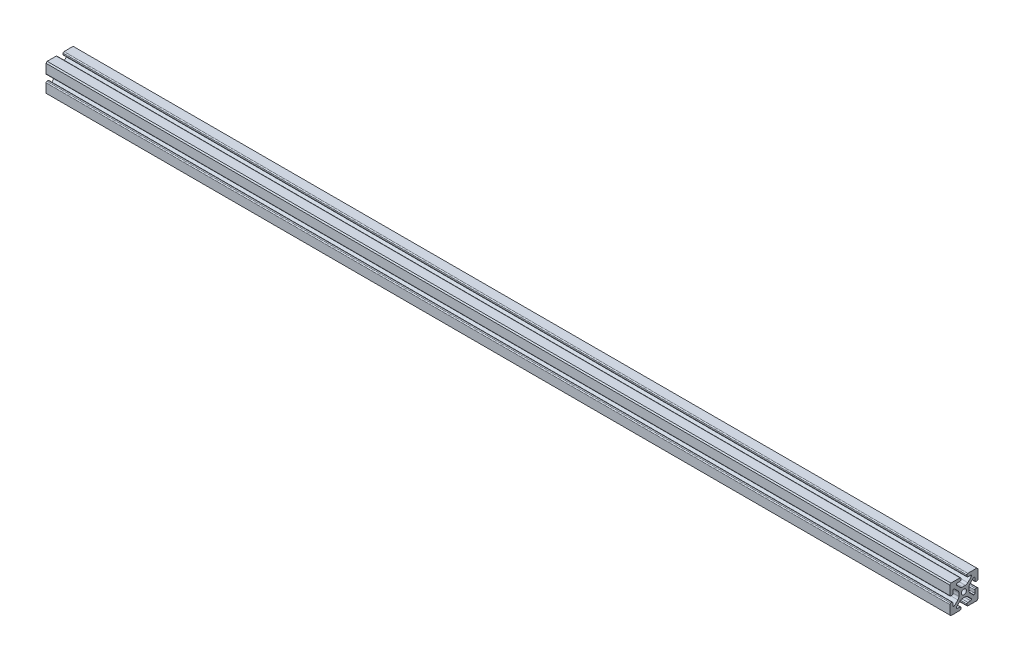
SolidWorks part; units mm, degrees
ref_plane "Front Plane" through (0, 0, 0) normal (0, 0, 1) x (1, 0, 0)
ref_plane "Top Plane" through (0, 0, 0) normal (0, 1, 0) x (1, 0, 0)
ref_plane "Right Plane" through (0, 0, 0) normal (1, 0, 0) x (0, 0, -1)
ref_plane "Plane1" through (0, 0, 0) normal (-1, 0, 0) x (0, -1, 0)
sketch "Sketch1" plane through (0, 0, 0) normal (-1, 0, 0) x (0, -1, 0)
  line L0 (19.05, 5.334) -> (19.05, 17.526)
  line L1 (19.05, 17.526) -> (17.526, 19.05)
  line L2 (17.526, 19.05) -> (5.334, 19.05)
  line L3 (4.064, 17.78) -> (4.064, 16.1266)
  line L4 (5.334, 14.8566) -> (9.0964, 14.8566)
  line L5 (10.287, 13.666) -> (10.287, 13.6538)
  line L6 (9.9383, 12.8119) -> (5.2776, 8.1513)
  line L7 (1.91, 6.7564) -> (-1.91, 6.7564)
  line L8 (-5.2776, 8.1513) -> (-9.9383, 12.8119)
  line L9 (-10.287, 13.6538) -> (-10.287, 13.666)
  line L10 (-9.0964, 14.8566) -> (-5.334, 14.8566)
  line L11 (-4.064, 16.1266) -> (-4.064, 17.78)
  line L12 (-5.334, 19.05) -> (-17.526, 19.05)
  line L13 (-17.526, 19.05) -> (-19.05, 17.526)
  line L14 (-19.05, 17.526) -> (-19.05, 5.334)
  line L15 (-17.78, 4.064) -> (-16.1266, 4.064)
  line L16 (-14.8566, 5.334) -> (-14.8566, 9.0964)
  line L17 (-13.666, 10.287) -> (-13.6538, 10.287)
  line L18 (-12.8119, 9.9383) -> (-8.1513, 5.2776)
  line L19 (-6.7564, 1.91) -> (-6.7564, -1.91)
  line L20 (-8.1513, -5.2776) -> (-12.8119, -9.9383)
  line L21 (-13.6538, -10.287) -> (-13.666, -10.287)
  line L22 (-14.8566, -9.0964) -> (-14.8566, -5.334)
  line L23 (-16.1266, -4.064) -> (-17.78, -4.064)
  line L24 (-19.05, -5.334) -> (-19.05, -17.526)
  line L25 (-19.05, -17.526) -> (-17.526, -19.05)
  line L26 (-17.526, -19.05) -> (-5.334, -19.05)
  line L27 (-4.064, -17.78) -> (-4.064, -16.1266)
  line L28 (-5.334, -14.8566) -> (-9.0964, -14.8566)
  line L29 (-10.287, -13.666) -> (-10.287, -13.6538)
  line L30 (-9.9383, -12.8119) -> (-5.2776, -8.1513)
  line L31 (-1.91, -6.7564) -> (1.91, -6.7564)
  line L32 (5.2776, -8.1513) -> (9.9383, -12.8119)
  line L33 (10.287, -13.6538) -> (10.287, -13.666)
  line L34 (9.0964, -14.8566) -> (5.334, -14.8566)
  line L35 (4.064, -16.1266) -> (4.064, -17.78)
  line L36 (5.334, -19.05) -> (17.526, -19.05)
  line L37 (17.526, -19.05) -> (19.05, -17.526)
  line L38 (19.05, -17.526) -> (19.05, -5.334)
  line L39 (17.78, -4.064) -> (16.1266, -4.064)
  line L40 (14.8566, -5.334) -> (14.8566, -9.0964)
  line L41 (13.666, -10.287) -> (13.6538, -10.287)
  line L42 (12.8119, -9.9383) -> (8.1513, -5.2776)
  line L43 (6.7564, -1.91) -> (6.7564, 1.91)
  line L44 (8.1513, 5.2776) -> (12.8119, 9.9383)
  line L45 (13.6538, 10.287) -> (13.666, 10.287)
  line L46 (14.8566, 9.0964) -> (14.8566, 5.334)
  line L47 (16.1266, 4.064) -> (17.78, 4.064)
  arc A0 (17.78, 4.064) -> (19.05, 5.334) centre (17.78, 5.334) ccw
  arc A1 (5.334, 19.05) -> (4.064, 17.78) centre (5.334, 17.78) ccw
  arc A2 (4.064, 16.1266) -> (5.334, 14.8566) centre (5.334, 16.1266) ccw
  arc A3 (9.0964, 14.8566) -> (10.287, 13.666) centre (9.0964, 13.666) cw
  arc A4 (10.287, 13.6538) -> (9.9383, 12.8119) centre (9.0964, 13.6538) cw
  arc A5 (5.2776, 8.1513) -> (1.91, 6.7564) centre (1.91, 11.5189) cw
  arc A6 (-1.91, 6.7564) -> (-5.2776, 8.1513) centre (-1.91, 11.5189) cw
  arc A7 (-9.9383, 12.8119) -> (-10.287, 13.6538) centre (-9.0964, 13.6538) cw
  arc A8 (-10.287, 13.666) -> (-9.0964, 14.8566) centre (-9.0964, 13.666) cw
  arc A9 (-5.334, 14.8566) -> (-4.064, 16.1266) centre (-5.334, 16.1266) ccw
  arc A10 (-4.064, 17.78) -> (-5.334, 19.05) centre (-5.334, 17.78) ccw
  arc A11 (-19.05, 5.334) -> (-17.78, 4.064) centre (-17.78, 5.334) ccw
  arc A12 (-16.1266, 4.064) -> (-14.8566, 5.334) centre (-16.1266, 5.334) ccw
  arc A13 (-14.8566, 9.0964) -> (-13.666, 10.287) centre (-13.666, 9.0964) cw
  arc A14 (-13.6538, 10.287) -> (-12.8119, 9.9383) centre (-13.6538, 9.0964) cw
  arc A15 (-8.1513, 5.2776) -> (-6.7564, 1.91) centre (-11.5189, 1.91) cw
  arc A16 (-6.7564, -1.91) -> (-8.1513, -5.2776) centre (-11.5189, -1.91) cw
  arc A17 (-12.8119, -9.9383) -> (-13.6538, -10.287) centre (-13.6538, -9.0964) cw
  arc A18 (-13.666, -10.287) -> (-14.8566, -9.0964) centre (-13.666, -9.0964) cw
  arc A19 (-14.8566, -5.334) -> (-16.1266, -4.064) centre (-16.1266, -5.334) ccw
  arc A20 (-17.78, -4.064) -> (-19.05, -5.334) centre (-17.78, -5.334) ccw
  arc A21 (-5.334, -19.05) -> (-4.064, -17.78) centre (-5.334, -17.78) ccw
  arc A22 (-4.064, -16.1266) -> (-5.334, -14.8566) centre (-5.334, -16.1266) ccw
  arc A23 (-9.0964, -14.8566) -> (-10.287, -13.666) centre (-9.0964, -13.666) cw
  arc A24 (-10.287, -13.6538) -> (-9.9383, -12.8119) centre (-9.0964, -13.6538) cw
  arc A25 (-5.2776, -8.1513) -> (-1.91, -6.7564) centre (-1.91, -11.5189) cw
  arc A26 (1.91, -6.7564) -> (5.2776, -8.1513) centre (1.91, -11.5189) cw
  arc A27 (9.9383, -12.8119) -> (10.287, -13.6538) centre (9.0964, -13.6538) cw
  arc A28 (10.287, -13.666) -> (9.0964, -14.8566) centre (9.0964, -13.666) cw
  arc A29 (5.334, -14.8566) -> (4.064, -16.1266) centre (5.334, -16.1266) ccw
  arc A30 (4.064, -17.78) -> (5.334, -19.05) centre (5.334, -17.78) ccw
  arc A31 (19.05, -5.334) -> (17.78, -4.064) centre (17.78, -5.334) ccw
  arc A32 (16.1266, -4.064) -> (14.8566, -5.334) centre (16.1266, -5.334) ccw
  arc A33 (14.8566, -9.0964) -> (13.666, -10.287) centre (13.666, -9.0964) cw
  arc A34 (13.6538, -10.287) -> (12.8119, -9.9383) centre (13.6538, -9.0964) cw
  arc A35 (8.1513, -5.2776) -> (6.7564, -1.91) centre (11.5189, -1.91) cw
  arc A36 (6.7564, 1.91) -> (8.1513, 5.2776) centre (11.5189, 1.91) cw
  arc A37 (12.8119, 9.9383) -> (13.6538, 10.287) centre (13.6538, 9.0964) cw
  arc A38 (13.666, 10.287) -> (14.8566, 9.0964) centre (13.666, 9.0964) cw
  arc A39 (14.8566, 5.334) -> (16.1266, 4.064) centre (16.1266, 5.334) ccw
  circle A40 centre (0, 0) radius 3.4036
extrude "Boss-Extrude1" add sketch "Sketch1" against normal blind 1219.2
